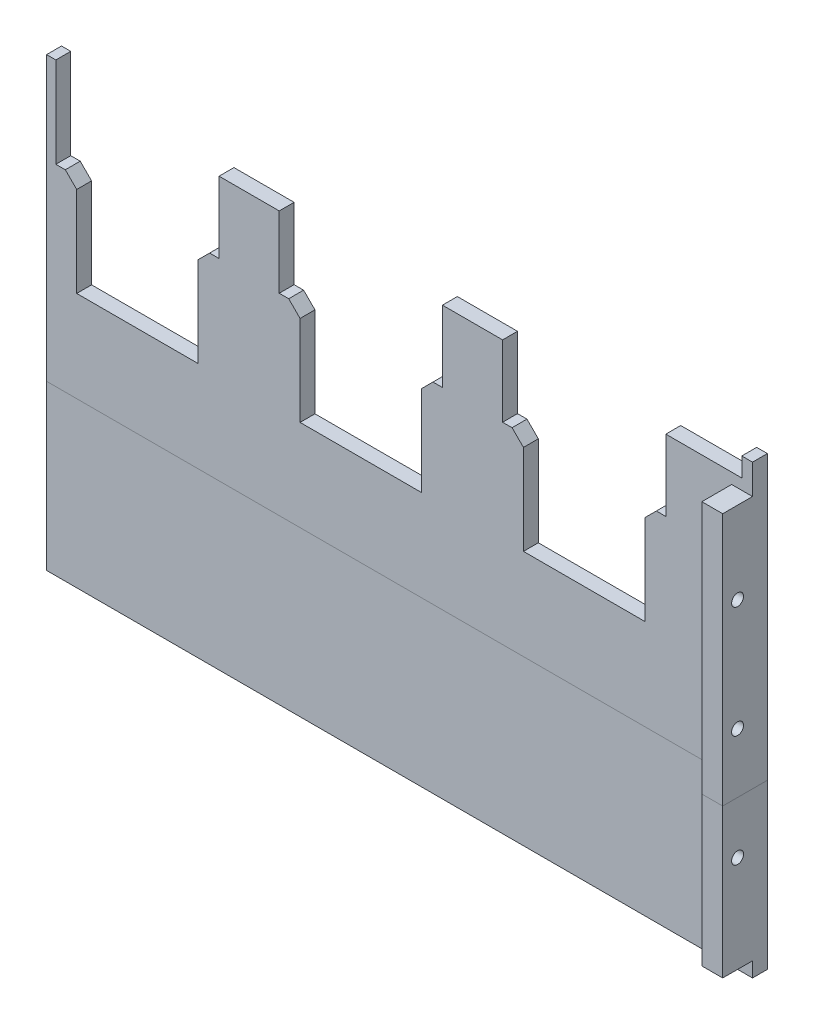
SolidWorks part; units mm, degrees
ref_plane "Płaszczyzna przednia" through (0, 0, 0) normal (0, 0, 1) x (1, 0, 0)
ref_plane "Płaszczyzna górna" through (0, 0, 0) normal (0, 1, 0) x (1, 0, 0)
ref_plane "Płaszczyzna prawa" through (0, 0, 0) normal (1, 0, 0) x (0, 0, -1)
sketch "Szkic1" plane through (0, 0, 0) normal (0, 0, 1) x (1, 0, 0)
  line L1 (-118.5, -75) -> (118.5, -75)
  line L2 (-118.5, -75) -> (-118.5, 75)
  line L3 (-118.5, 75) -> (118.5, 75)
  line L4 (118.5, -75) -> (118.5, 75)
  line L5 (0, 75) -> (0, -75) construction
  line L6 (-118.5, 0) -> (118.5, 0) construction
  point P0 (0, 0)
  dimension "D1" = 237
  dimension "D2" = 150
extrude "Dodanie-wyciągnięcie1" add sketch "Szkic1" along normal blind 5
sketch "Szkic2" plane through (0, 0, 5) normal (0, 0, 1) x (1, 0, 0)
  line L0 (118.5, -75) -> (118.5, 75) construction
  line L1 (118.5, 65) -> (111.5, 65)
  line L2 (118.5, 65) -> (118.5, -70)
  line L3 (118.5, -70) -> (111.5, -70)
  line L4 (111.5, 65) -> (111.5, -70)
  line L5 (115, -70) -> (115, 65) construction
  line L6 (118.5, -2.5) -> (111.5, -2.5) construction
  line L7 (118.5, 75) -> (-118.5, 75) construction
  line L8 (-118.5, -75) -> (118.5, -75) construction
  line L9 (0, 0) -> (0, 75) construction
  point P300 (115, -2.5)
  dimension "D1" = 10
  dimension "D2" = 5
  dimension "D3" = 7
extrude "Dodanie-wyciągnięcie2" add sketch "Szkic2" along normal blind 10
sketch "Szkic3" plane through (118.5, 0, 0) normal (1, 0, 0) x (0, 0, -1)
  line L0 (-10, 65) -> (-10, -70) construction
  line L1 (-15, 65) -> (-5, 65) construction
  line L2 (-15, -70) -> (-5, -70) construction
  line L3 (0, 0) -> (-15, 0) construction
  line L4 (0, -75) -> (0, 75) construction
  line L5 (-15, -70) -> (-15, 65) construction
  point P6 (-10, 37.5)
  point P7 (-10, 0)
  point P8 (-10, -37.5)
  dimension "D1" = 37.5
hole_wizard "Otwór Ø4.0 (4)1" positions "Szkic3" profile "Szkic4" hole size "Ø4.0" standard "DIN"
sketch "Szkic4" plane through (118.5, -37.5, 10) normal (0, 1, 0) x (0, 0, -1)
  line L0 (0, 0) -> (0, 6.7)
  line L1 (0, 6.7) -> (2, 6.7)
  line L2 (2, 6.7) -> (2, 0)
  line L5 (2, 0) -> (0, 0)
  line L10 (0, 6.7) -> (-2, 6.7) construction
  line L11 (0, -6.35) -> (0, 107.95) construction
  dimension "Średnica otworu" = 4
  dimension "Głębokość otworu" = 6.7
  dimension "Kąt wiertła" = 180
ref_plane "Płaszczyzna1" through (0, 0, 0) normal (-1, 0, 0) x (0, 0, 1)
sketch "Szkic5" plane through (0, 0, 0) normal (0, 0, -1) x (-1, 0, 0)
  line L0 (-86, 45.0546) -> (-86, 45)
  line L1 (111, 44) -> (112, 45) construction
  line L2 (112, 45) -> (112, 51) construction
  line L3 (-89, 65) -> (-89, 69)
  line L4 (108, 41) -> (111, 44) construction
  line L5 (-35, 65) -> (-35, 69)
  line L6 (61, 65) -> (61, 45.0546) construction
  line L7 (61, 45.0546) -> (67.7879, 45.0546) construction
  line L8 (-14, 65) -> (-14, 69)
  line L9 (40, 65) -> (40, 69)
  line L10 (61, 65) -> (61, 69)
  line L11 (115, 65) -> (115, 75)
  line L12 (-118.5, 75) -> (118.5, 75) construction
  line L13 (115, 75) -> (65.5, 75)
  line L14 (35.5, 75) -> (-9.5, 75)
  line L15 (108.2121, 45.0546) -> (115, 45.0546) construction
  line L16 (115, 45.0546) -> (115, 65) construction
  line L18 (64, 45) -> (65, 44) construction
  line L19 (-11, 45.0546) -> (-11, 45)
  line L20 (-39.5, 75) -> (-84.5, 75)
  line L21 (-82.4, 10.6) -> (-41.6, 10.6)
  line L22 (65, 44) -> (68, 41) construction
  line L23 (-41.6, 10.6) -> (-41.6, 40.8343)
  line L24 (-41.6, 40.8343) -> (-38.7172, 43.7172)
  line L25 (-38.7172, 43.7172) -> (-37.7797, 44.6546)
  line L26 (-37.7797, 44.6546) -> (-37.7797, 44.6546)
  line L27 (-37.7797, 44.6546) -> (-34.6, 44.6546)
  line L29 (-34.6, 44.6546) -> (-34.6, 65)
  line L30 (-34.6, 65) -> (-34.6, 68.6)
  line L31 (-34.6, 68.6) -> (-14.4, 68.6)
  line L32 (-14.4, 65) -> (-14.4, 68.6)
  line L33 (-14.4, 65) -> (-14.4, 44.6546)
  line L35 (-14.4, 44.6546) -> (-11.2203, 44.6546)
  line L37 (-11.2203, 44.6546) -> (-11.2203, 44.6546)
  line L38 (-11.2203, 44.6546) -> (-10.2828, 43.7172)
  line L39 (68, 41) -> (68, 11) construction
  line L40 (68, 11) -> (108, 11) construction
  line L41 (108, 11) -> (108, 41) construction
  line L42 (-10.2828, 43.7172) -> (-7.4, 40.8343)
  line L43 (36, 44) -> (37, 45) construction
  line L44 (37, 45) -> (37, 51) construction
  line L45 (-7.4, 40.8343) -> (-7.4, 10.6)
  line L46 (33, 41) -> (36, 44) construction
  line L47 (-7.4, 10.6) -> (33.4, 10.6)
  line L48 (-14, 65) -> (-14, 45.0546) construction
  line L49 (-14, 45.0546) -> (-7.2121, 45.0546) construction
  line L50 (33.4, 10.6) -> (33.4, 40.8343)
  line L51 (33.4, 40.8343) -> (36.2828, 43.7172)
  line L52 (36.2828, 43.7172) -> (37.2203, 44.6546)
  line L53 (37.2203, 44.6546) -> (37.2203, 44.6546)
  line L54 (37.2203, 44.6546) -> (40.4, 44.6546)
  line L55 (40.4, 44.6546) -> (40.4, 65)
  line L56 (40.4, 65) -> (40.4, 68.6)
  line L57 (33.2121, 45.0546) -> (40, 45.0546) construction
  line L58 (40, 45.0546) -> (40, 65) construction
  line L60 (-11, 45) -> (-10, 44) construction
  line L61 (40.4, 68.6) -> (60.6, 68.6)
  line L62 (60.6, 65) -> (60.6, 68.6)
  line L63 (60.6, 65) -> (60.6, 44.6546)
  line L64 (-10, 44) -> (-7, 41) construction
  line L65 (60.6, 44.6546) -> (63.7797, 44.6546)
  line L66 (63.7797, 44.6546) -> (63.7797, 44.6546)
  line L67 (63.7797, 44.6546) -> (64.7172, 43.7172)
  line L68 (64.7172, 43.7172) -> (67.6, 40.8343)
  line L69 (67.6, 40.8343) -> (67.6, 10.6)
  line L70 (67.6, 10.6) -> (108.4, 10.6)
  line L71 (108.4, 10.6) -> (108.4, 40.8343)
  line L72 (108.4, 40.8343) -> (111.2828, 43.7172)
  line L73 (111.2828, 43.7172) -> (112.2203, 44.6546)
  line L74 (112.2203, 44.6546) -> (112.2203, 44.6546)
  line L75 (112.2203, 44.6546) -> (115.4, 44.6546)
  line L76 (115.4, 44.6546) -> (115.4, 65)
  line L77 (115.4, 65) -> (115.4, 75.4)
  line L78 (115.4, 75.4) -> (65.5, 75.4)
  line L79 (65.5, 75.4) -> (35.5, 75.4)
  line L80 (35.5, 75.4) -> (-9.5, 75.4)
  line L81 (-7, 41) -> (-7, 11) construction
  line L82 (-7, 11) -> (33, 11) construction
  line L83 (33, 11) -> (33, 41) construction
  line L84 (-9.5, 75.4) -> (-39.5, 75.4)
  line L85 (-39, 44) -> (-38, 45) construction
  line L86 (-38, 45) -> (-38, 51) construction
  line L87 (-39.5, 75.4) -> (-84.5, 75.4)
  line L88 (-42, 41) -> (-39, 44) construction
  line L89 (-84.5, 75.4) -> (-114.9, 75.4)
  line L90 (-86, 45) -> (-85, 44) construction
  line L91 (-114.9, 75.4) -> (-114.9, 68.6)
  line L92 (-114.9, 68.6) -> (-89.4, 68.6)
  line L93 (-89.4, 65) -> (-89.4, 68.6)
  line L94 (-85, 44) -> (-82, 41) construction
  line L95 (-89.4, 65) -> (-89.4, 44.6546)
  line L96 (-89.4, 44.6546) -> (-86.2203, 44.6546)
  line L97 (-86.2203, 44.6546) -> (-86.2203, 44.6546)
  line L98 (-86.2203, 44.6546) -> (-85.2828, 43.7172)
  line L99 (-85.2828, 43.7172) -> (-82.4, 40.8343)
  line L100 (-82.4, 40.8343) -> (-82.4, 10.6)
  line L111 (-82, 41) -> (-82, 11) construction
  line L112 (-82, 11) -> (-42, 11) construction
  line L113 (-42, 11) -> (-42, 41) construction
  line L114 (-89, 65) -> (-89, 45.0546) construction
  line L115 (-89, 45.0546) -> (-82.2121, 45.0546) construction
  line L123 (-41.7879, 45.0546) -> (-35, 45.0546) construction
  line L124 (-35, 45.0546) -> (-35, 65) construction
  line L126 (-84.5, 75) -> (-114.5, 75)
  line L128 (35.5, 69) -> (65.5, 69) construction
  line L132 (-39.5, 69) -> (-9.5, 69) construction
  line L134 (-114.5, 93) -> (-114.5, 69) construction
  line L135 (-114.5, 69) -> (-84.5, 69) construction
  line L137 (-9.5, 75) -> (-39.5, 75)
  line L139 (111, 44) -> (112, 45)
  line L140 (112, 45) -> (112, 45.0546)
  line L142 (108, 41) -> (111, 44)
  line L144 (61, 65) -> (61, 45.0546)
  line L145 (61, 45.0546) -> (64, 45.0546)
  line L153 (112, 45.0546) -> (115, 45.0546)
  line L154 (115, 45.0546) -> (115, 65)
  line L156 (64, 45) -> (65, 44)
  line L158 (64, 45.0546) -> (64, 45)
  line L160 (65, 44) -> (68, 41)
  line L177 (68, 41) -> (68, 11)
  line L178 (68, 11) -> (108, 11)
  line L179 (108, 11) -> (108, 41)
  line L181 (36, 44) -> (37, 45)
  line L182 (37, 45) -> (37, 45.0546)
  line L184 (33, 41) -> (36, 44)
  line L186 (-14, 65) -> (-14, 45.0546)
  line L187 (-14, 45.0546) -> (-11, 45.0546)
  line L195 (37, 45.0546) -> (40, 45.0546)
  line L196 (40, 45.0546) -> (40, 65)
  line L198 (-11, 45) -> (-10, 44)
  line L202 (-10, 44) -> (-7, 41)
  line L219 (-7, 41) -> (-7, 11)
  line L220 (-7, 11) -> (33, 11)
  line L221 (33, 11) -> (33, 41)
  line L223 (-39, 44) -> (-38, 45)
  line L224 (-38, 45) -> (-38, 45.0546)
  line L226 (-42, 41) -> (-39, 44)
  line L228 (-86, 45) -> (-85, 44)
  line L232 (-85, 44) -> (-82, 41)
  line L249 (-82, 41) -> (-82, 11)
  line L250 (-82, 11) -> (-42, 11)
  line L251 (-42, 11) -> (-42, 41)
  line L252 (-89, 65) -> (-89, 45.0546)
  line L253 (-89, 45.0546) -> (-86, 45.0546)
  line L261 (-38, 45.0546) -> (-35, 45.0546)
  line L262 (-35, 45.0546) -> (-35, 65)
  line L266 (40, 69) -> (61, 69)
  line L270 (-35, 69) -> (-14, 69)
  line L272 (-114.5, 75) -> (-114.5, 69)
  line L273 (-114.5, 69) -> (-89, 69)
  line L280 (-118.5, 75) -> (-118.5, -75)
  line L281 (-118.5, -75) -> (118.5, -75)
  line L282 (118.5, -75) -> (118.5, 75)
  line L283 (118.5, 75) -> (-118.5, 75)
  line L287 (65.5, 75) -> (35.5, 75)
  line M8 (118.5, 75) -> (-118.5, 75)
  dimension "D1" = 0
  dimension "D2" = 0.4
extrude "Wytnij-wyciągnięcie1" cut sketch "Szkic5" against normal up to next contours L272 L273 L3 L252 L253 L0 L228 L232 L249 L250 L251 L226 L223 L224 L261 L262 L5 L270 L8 L186 L187 L19 L198 L202 L219 L220 L221 L184 L181 L182 L195 L196 L9 L266 L10 L144 L145 L158 L156 L160 L177 L178 L179 L142 L139 L140 L153 L154 L11 M8 | L273 L272 L91 L92 L93 L95 L96 L98 L99 L100 L21 L23 L24 L25 L27 L29 L30 L31 L32 L33 L35 L38 L42 L45 L47 L50 L51 L52 L54 L55 L56 L61 L62 L63 L65 L67 L68 L69 L70 L71 L72 L73 L75 L76 L77 L11 L154 L153 L140 M8
ref_plane "Płaszczyzna2" through (0, -20, 0) normal (0, -1, 0) x (-1, 0, 0)
split "Podziel1" trim tools "Płaszczyzna2" bodies to split 106 resulting bodies 107 108
sketch "Szkic6" plane through (0, -70, 0) normal (0, -1, 0) x (1, 0, 0)
  line L0 (111.5, 15) -> (118.5, 5) construction
  point P4 (115, 10)
hole_wizard "Otwory ustalające Ø4.0mm1" positions "Szkic6" profile "Szkic7" hole size "Ø4.0" standard "DIN"
sketch "Szkic7" plane through (115, -70, 10) normal (1, 0, 0) x (0, 0, -1)
  line L0 (0, 0) -> (0, 6.7)
  line L1 (0, 6.7) -> (2, 6.7)
  line L2 (2, 6.7) -> (2, 0)
  line L5 (2, 0) -> (0, 0)
  line L10 (0, 6.7) -> (-2, 6.7) construction
  line L11 (0, -6.35) -> (0, 107.95) construction
  dimension "Średnica otworu" = 4
  dimension "Głębokość otworu" = 6.7
  dimension "Kąt wiertła" = 180
